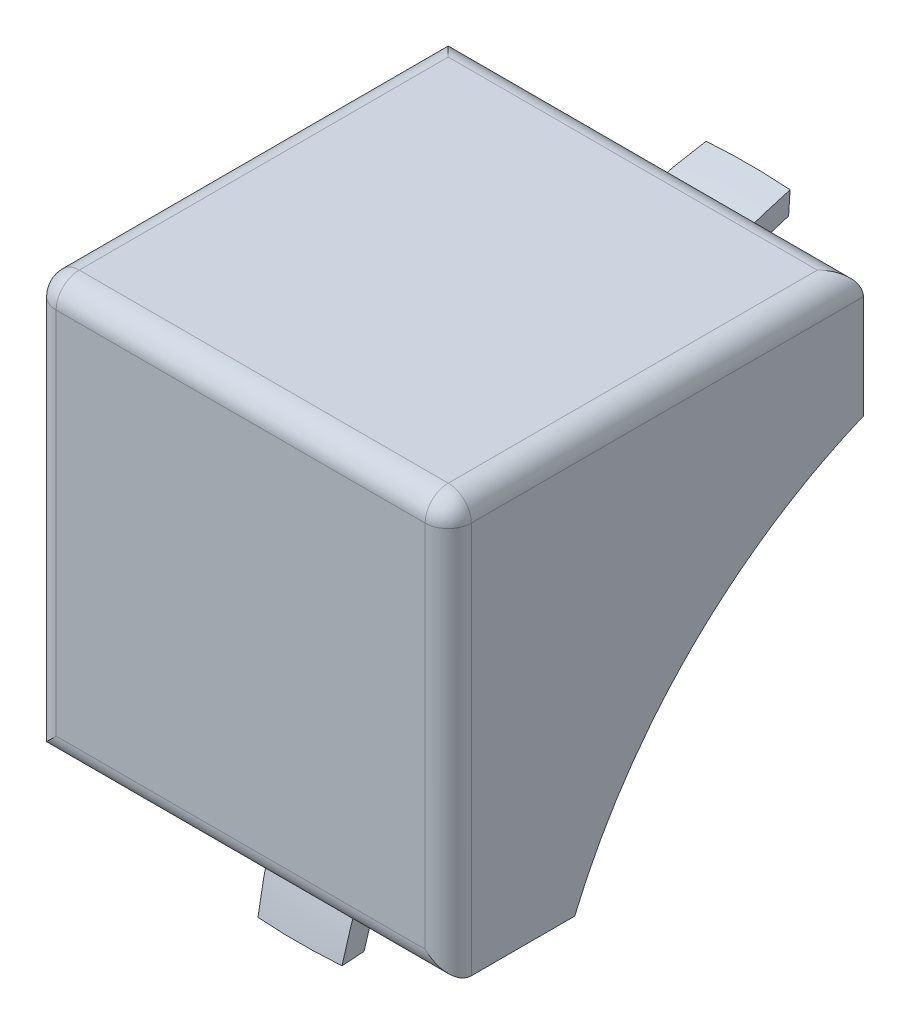
SolidWorks part; units mm, degrees
ref_plane "前视基准面" through (0, 0, 0) normal (0, 0, 1) x (1, 0, 0)
ref_plane "上视基准面" through (0, 0, 0) normal (0, 1, 0) x (1, 0, 0)
ref_plane "右视基准面" through (0, 0, 0) normal (1, 0, 0) x (0, 0, -1)
sketch "草图1" plane through (0, 0, 0) normal (0, 0, 1) x (1, 0, 0)
  line L1 (-27, 27) -> (27, 27)
  line L2 (-27, 27) -> (-27, -27)
  line L3 (-27, -27) -> (27, -27)
  line L4 (27, 27) -> (27, -27)
  line L5 (-27, 27) -> (27, -27) construction
  line L6 (-27, -27) -> (27, 27) construction
  point P0 (0, 0)
  dimension "D1" = 54
  dimension "D2" = 54
extrude "凸台-拉伸1" add sketch "草图1" along normal mid plane 54
ref_plane "基准面1" through (0, 0, 27) normal (0, 0, 1) x (1, 0, 0)
sketch "草图2" plane through (0, 0, 27) normal (0, 0, 1) x (1, 0, 0)
  line L0 (27, 27) -> (-27, 27) construction
  line L1 (-27, 27) -> (-27, -27) construction
  line L2 (27, -27) -> (27, 27) construction
  line L3 (-9, 27) -> (-27, 27)
  line L4 (-27, 27) -> (-27, -27)
  line L5 (-27, -27) -> (27, -27)
  line L6 (27, -27) -> (27, 27)
  line L7 (27, 27) -> (9, 27)
  line L8 (9, 27) -> (9, 9)
  line L9 (9, 9) -> (-9, 9)
  line L10 (-9, 9) -> (-9, 27)
  point P0 (-9, 27)
  point P5 (9, 27)
  dimension "D1" = 18
  dimension "D2" = 18
  dimension "D3" = 18
extrude "切除-拉伸1" cut sketch "草图2" against normal blind 54
ref_plane "基准面2" through (0, 27, 0) normal (0, 1, 0) x (1, 0, 0)
sketch "草图3" plane through (0, 27, 0) normal (0, 1, 0) x (1, 0, 0)
  line L0 (9, 27) -> (9, -27) construction
  line L1 (-9, 27) -> (9, 27)
  line L2 (-9, 27) -> (-9, -9)
  line L3 (-9, -9) -> (9, -9)
  line L4 (9, 27) -> (9, -9)
  line L5 (-9.9, -27) -> (9.9, -27) construction
  dimension "D1" = 18
extrude "切除-拉伸2" cut sketch "草图3" against normal through all
sketch "草图4" plane through (0, 0, 0) normal (1, 0, 0) x (0, 0, -1)
  line L0 (0, 25) -> (0, -25)
  arc A0 (0, 25) -> (0, -25) centre (0, 0) ccw
  dimension "D1" = 50
revolve "切除-旋转1" cut sketch "草图4" angle 360 about L0
sketch "草图5" plane through (0, 0, 0) normal (1, 0, 0) x (0, 0, -1)
  line L0 (0, 25) -> (0, 24)
  line L1 (-24, 0) -> (-25, 0)
  line L2 (0, 0) -> (15.3918, 15.3918) construction
  arc A0 (0, 25) -> (-25, 0) centre (0, 0) ccw
  arc A1 (0, 24) -> (-24, 0) centre (0, 0) ccw
  dimension "D1" = 50
  dimension "D2" = 48
revolve "旋转3" add sketch "草图5" angle 10 mid plane about L2
ref_plane "基准面4" through (0, 5, 0) normal (0, 1, 0) x (1, 0, 0)
sketch "草图7" plane through (0, 5, 0) normal (0, 1, 0) x (1, 0, 0)
  line L1 (-9.2851, -27.3092) -> (9.4708, -27.3092)
  line L2 (-9.2851, -27.3092) -> (-9.2851, 0.2677)
  line L3 (-9.2851, 0.2677) -> (9.4708, 0.2677)
  line L4 (9.4708, -27.3092) -> (9.4708, 0.2677)
extrude "切除-拉伸3" cut sketch "草图7" against normal through all
ref_plane "基准面5" through (0, 0, 5) normal (0, 0, 1) x (1, 0, 0)
sketch "草图8" plane through (0, 0, 5) normal (0, 0, 1) x (1, 0, 0)
  line L1 (-9.5398, 27.3773) -> (9.5146, 27.3773)
  line L2 (-9.5398, 27.3773) -> (-9.5398, 4.3962)
  line L3 (-9.5398, 4.3962) -> (9.5146, 4.3962)
  line L4 (9.5146, 27.3773) -> (9.5146, 4.3962)
extrude "切除-拉伸4" cut sketch "草图8" against normal through all
fillet "圆角1" radius 1 7 edges at (0, 9, 27) (-9, 18, 27) (0, 27, 9) (0, 27, 27) (9, 27, 18) (-9, 27, 18) (9, 18, 27)
scale "缩放比例1" bodies to scale 114 109 scale about origin uniform scaling yes scale factor 2.083333
